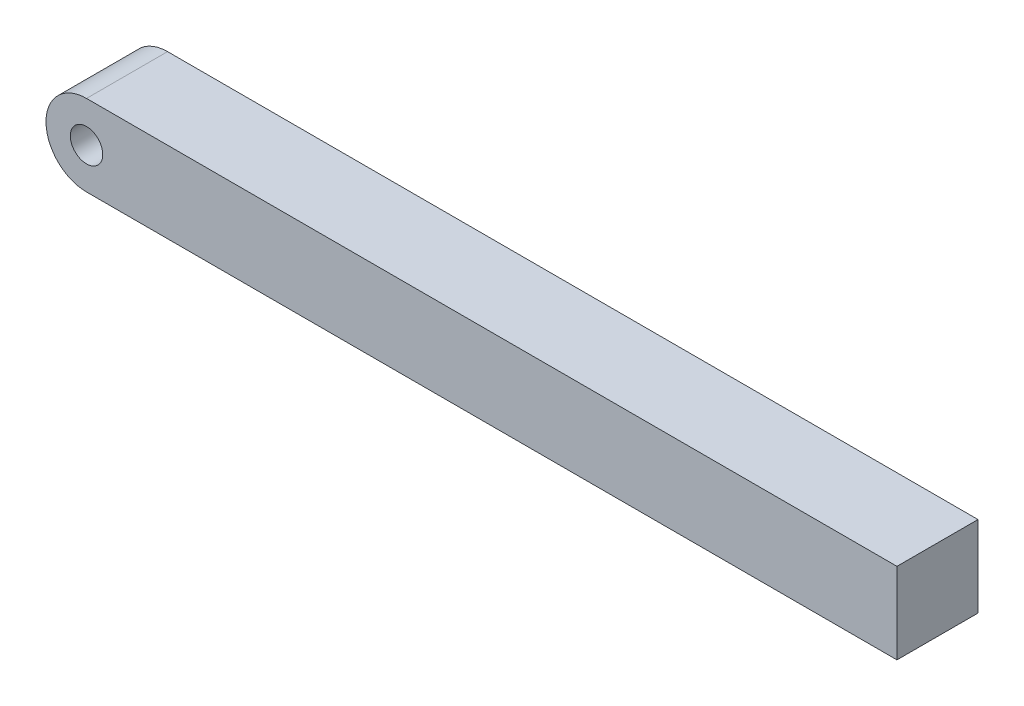
SolidWorks part; units mm, degrees
ref_plane "正面" through (0, 0, 0) normal (0, 0, 1) x (1, 0, 0)
ref_plane "平面" through (0, 0, 0) normal (0, 1, 0) x (1, 0, 0)
ref_plane "右側面" through (0, 0, 0) normal (1, 0, 0) x (0, 0, -1)
sketch "ｽｹｯﾁ1" plane through (0, 0, 0) normal (0, 0, 1) x (1, 0, 0)
  line L1 (-500, -50) -> (500, -50)
  line L2 (-500, -50) -> (-500, 50)
  line L3 (-500, 50) -> (500, 50)
  line L4 (500, -50) -> (500, 50)
  line L5 (-500, -50) -> (500, 50) construction
  line L6 (-500, 50) -> (500, -50) construction
  circle A0 centre (-500, 0) radius 50
  circle A1 centre (-500, 0) radius 20
  point P0 (0, 0)
extrude "ﾎﾞｽ - 押し出し1" add sketch "ｽｹｯﾁ1" along normal blind 100 contours A1 L2 A0 | A1 L2 A0 | A0 L1 L4 L3
